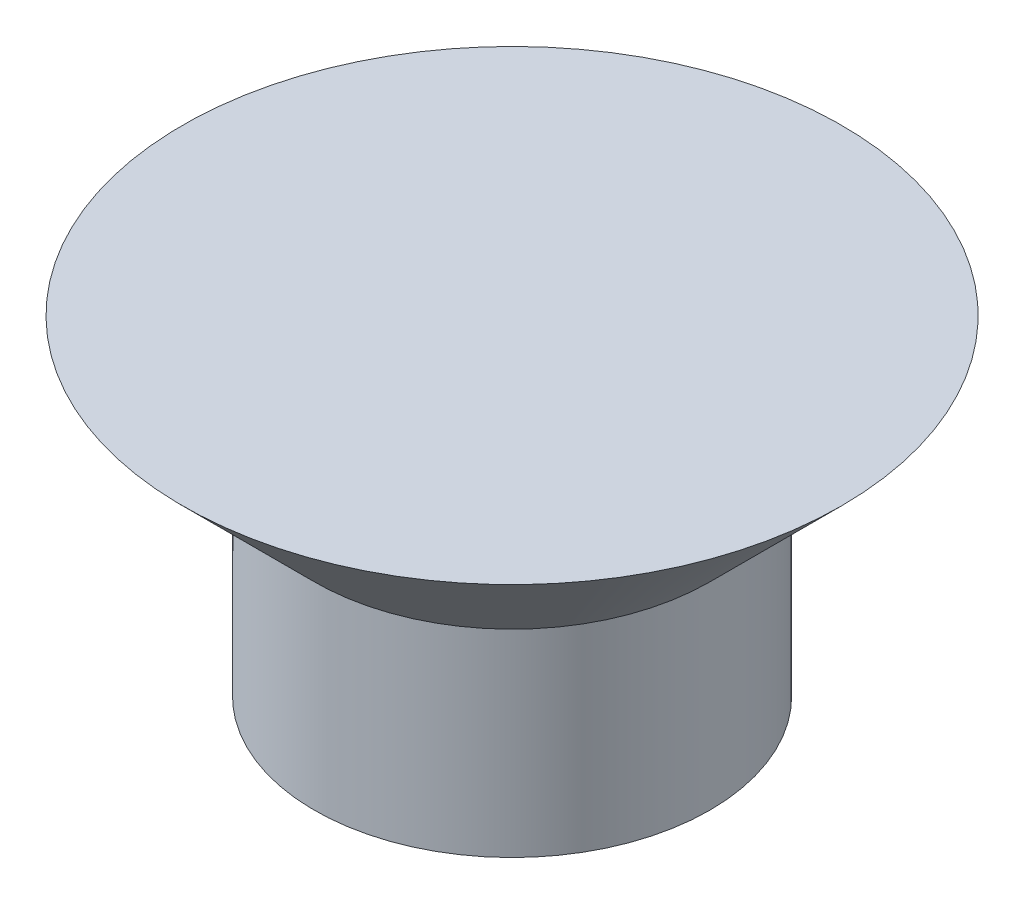
SolidWorks part; units mm, degrees
ref_plane "Front Plane" through (0, 0, 0) normal (0, 0, 1) x (1, 0, 0)
ref_plane "Top Plane" through (0, 0, 0) normal (0, 1, 0) x (1, 0, 0)
ref_plane "Right Plane" through (0, 0, 0) normal (1, 0, 0) x (0, 0, -1)
sketch "Sketch1" plane through (0, 0, 0) normal (0, 0, 1) x (1, 0, 0)
  line L0 (0, 0) -> (0, 2.5)
  line L1 (0, 2.5) -> (2.5, 2.5)
  line L2 (2.5, 2.5) -> (1.5, 1.5)
  line L3 (1.5, 1.5) -> (1.5, 0)
  line L4 (1.5, 0) -> (0, 0)
  dimension "D1" = 2.5
  dimension "D2" = 1.5
  dimension "D3" = 2.5
  dimension "D4" = 1.5
revolve "Revolve1" add sketch "Sketch1" angle 360 about L0
sketch "Orientation Sketch" plane through (0, 2.5, 0) normal (0, 1, 0) x (1, 0, 0)
  circle A0 centre (0, 0) radius 2.5 construction
  circle A1 centre (0, 0) radius 2.5
  point P3 (0, 0)
other "FormTool1"
